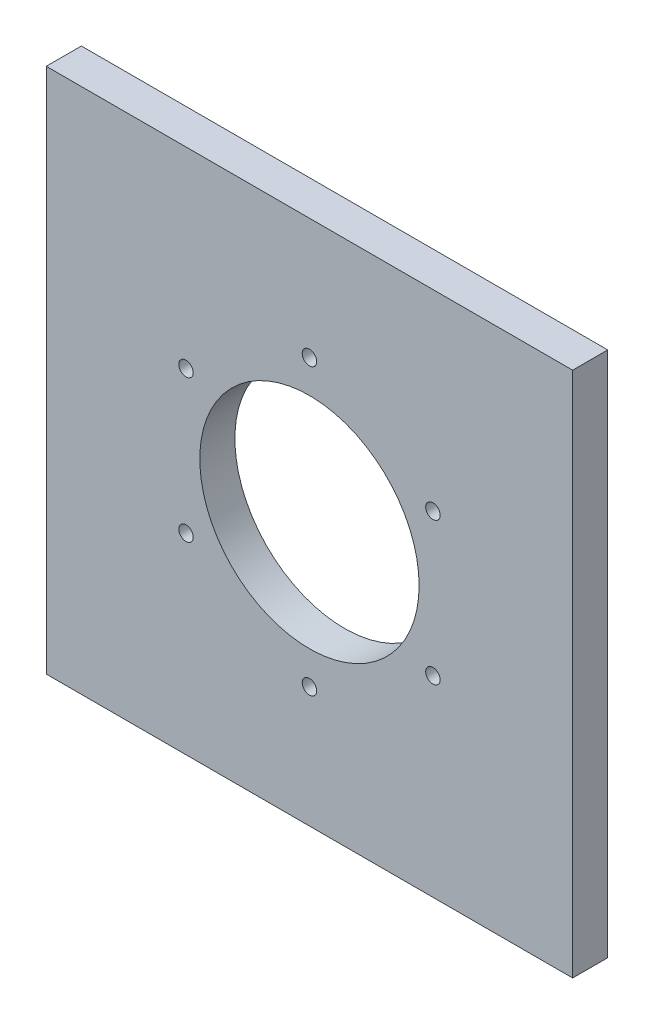
SolidWorks part; units mm, degrees
material "Alumina"
ref_plane "Front Plane" through (0, 0, 0) normal (0, 0, 1) x (1, 0, 0)
ref_plane "Top Plane" through (0, 0, 0) normal (0, 1, 0) x (1, 0, 0)
ref_plane "Right Plane" through (0, 0, 0) normal (1, 0, 0) x (0, 0, -1)
sketch "Sketch1" plane through (0, 0, 0) normal (0, 0, 1) x (1, 0, 0)
  line L1 (-60, 60) -> (60, 60)
  line L2 (-60, 60) -> (-60, -60)
  line L3 (-60, -60) -> (60, -60)
  line L4 (60, 60) -> (60, -60)
  line L5 (-60, 60) -> (60, -60) construction
  line L6 (-60, -60) -> (60, 60) construction
  circle A0 centre (0, 0) radius 25
  point P0 (0, 0)
  dimension "D3" = 50
  dimension "D1" = 120
  dimension "D2" = 120
extrude "Boss-Extrude1" add sketch "Sketch1" along normal blind 8
sketch "Sketch2" plane through (0, 0, 0) normal (0, 0, 1) x (1, 0, 0)
  circle A0 centre (0, 0) radius 32.5 construction
  circle A1 centre (0, 32.5) radius 1.65
  dimension "D1" = 3.3
extrude "Cut-Extrude2" cut sketch "Sketch2" along normal through all
pattern_circular "CirPattern1" count 6 over 360 about axis through (0, 0, 0) along (0, 0, 1) of "Cut-Extrude2"
